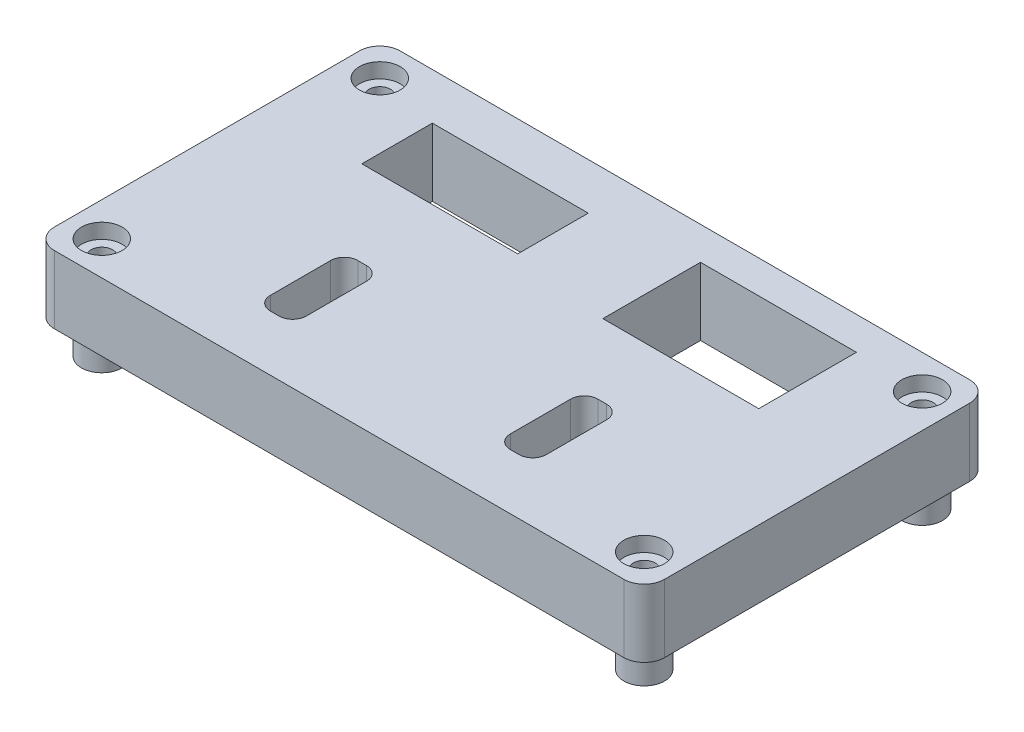
SolidWorks part; units mm, degrees
ref_plane "Front" through (0, 0, 0) normal (0, 0, 1) x (1, 0, 0)
ref_plane "Top" through (0, 0, 0) normal (0, 1, 0) x (1, 0, 0)
ref_plane "Right" through (0, 0, 0) normal (1, 0, 0) x (0, 0, -1)
sketch "ｽｹｯﾁ1" plane through (0, 0, 0) normal (0, 1, 0) x (1, 0, 0)
  line L0 (14.6, 38.95) -> (37.6, 38.95) construction
  line L1 (0, 0) -> (90, 0)
  line L2 (0, 0) -> (0, 51)
  line L3 (0, 51) -> (90, 51)
  line L4 (90, 0) -> (90, 51)
  line L5 (14.6, 44.15) -> (37.6, 44.15)
  line L6 (14.6, 44.15) -> (14.6, 33.75)
  line L7 (14.6, 33.75) -> (37.6, 33.75)
  line L8 (37.6, 44.15) -> (37.6, 33.75)
  line L9 (52.15, 46.15) -> (75.15, 46.15)
  line L10 (52.15, 46.15) -> (52.15, 31.75)
  line L11 (52.15, 31.75) -> (75.15, 31.75)
  line L12 (75.15, 46.15) -> (75.15, 31.75)
  line L13 (52.15, 38.95) -> (75.15, 38.95) construction
  line L14 (45, 51) -> (45, 0) construction
  line L15 (0, 25.5) -> (90, 25.5) construction
  line L16 (24.65, 21.1) -> (24.65, 8.2)
  line L17 (60.05, 21.1) -> (65.35, 21.1)
  line L18 (60.05, 21.1) -> (60.05, 8.2)
  line L19 (60.05, 8.2) -> (65.35, 8.2)
  line L20 (65.35, 21.1) -> (65.35, 8.2)
  line L21 (29.95, 8.2) -> (24.65, 8.2)
  line L22 (29.95, 21.1) -> (29.95, 8.2)
  line L23 (29.95, 21.1) -> (24.65, 21.1)
  circle A0 centre (5, 46) radius 1.6
  circle A1 centre (85, 46) radius 1.6
  circle A2 centre (85, 5) radius 1.6
  circle A3 centre (5, 5) radius 1.6
  dimension "D10" = 3.2
  dimension "D11" = 5
  dimension "D1" = 90
  dimension "D2" = 51
  dimension "D3" = 14.6
  dimension "D4" = 10.4
  dimension "D5" = 23
  dimension "D6" = 6.85
  dimension "D7" = 23
  dimension "D8" = 14.4
  dimension "D9" = 14.85
  dimension "D12" = 5
  dimension "D13" = 12.9
  dimension "D14" = 5.3
  dimension "D15" = 24.65
  dimension "D16" = 8.2
extrude "ﾎﾞｽ - 押し出し1" add sketch "ｽｹｯﾁ1" along normal blind 10
fillet "ﾌｨﾚｯﾄ1" radius 2 8 edges at (65.35, 5, -8.2) (60.05, 5, -8.2) (65.35, 5, -21.1) (60.05, 5, -21.1) (29.95, 5, -8.2) (24.65, 5, -8.2) (24.65, 5, -21.1) (29.95, 5, -21.1)
sketch "ｽｹｯﾁ2" plane through (0, 0, 0) normal (0, -1, 0) x (1, 0, 0)
  line L0 (45, 0) -> (45, -51) construction
  line L1 (0, 0) -> (90, 0) construction
  line L2 (90, -51) -> (0, -51) construction
  line L3 (0, -25.5) -> (90, -25.5) construction
  line L4 (0, -51) -> (0, 0) construction
  line L5 (90, 0) -> (90, -51) construction
  circle A0 centre (5, -5) radius 3
  circle A1 centre (85, -5) radius 3
  circle A2 centre (85, -46) radius 3
  circle A3 centre (5, -46) radius 3
  circle A4 centre (5, -5) radius 1.6
  circle A5 centre (85, -5) radius 1.6
  circle A6 centre (85, -46) radius 1.6
  circle A7 centre (5, -46) radius 1.6
  dimension "D1" = 6
  dimension "D2" = 3.2
extrude "ﾎﾞｽ - 押し出し2" add sketch "ｽｹｯﾁ2" along normal blind 5
fillet "ﾌｨﾚｯﾄ2" radius 3 4 edges at (0, 5, -51) (90, 5, -51) (90, 5, 0) (0, 5, 0)
sketch "ｽｹｯﾁ3" plane through (0, 10, 0) normal (0, 1, 0) x (1, 0, 0)
  line L0 (45, 51) -> (45, 0) construction
  line L1 (87, 51) -> (3, 51) construction
  line L2 (3, 0) -> (87, 0) construction
  line L3 (0, 25.5) -> (90, 25.5) construction
  line L4 (0, 48) -> (0, 3) construction
  line L5 (90, 3) -> (90, 48) construction
  circle A0 centre (5, 46) radius 3
  circle A1 centre (85, 46) radius 3
  circle A2 centre (85, 5) radius 3
  circle A3 centre (5, 5) radius 3
  dimension "D1" = 6
extrude "ｶｯﾄ - 押し出し1" cut sketch "ｽｹｯﾁ3" against normal blind 2.2
